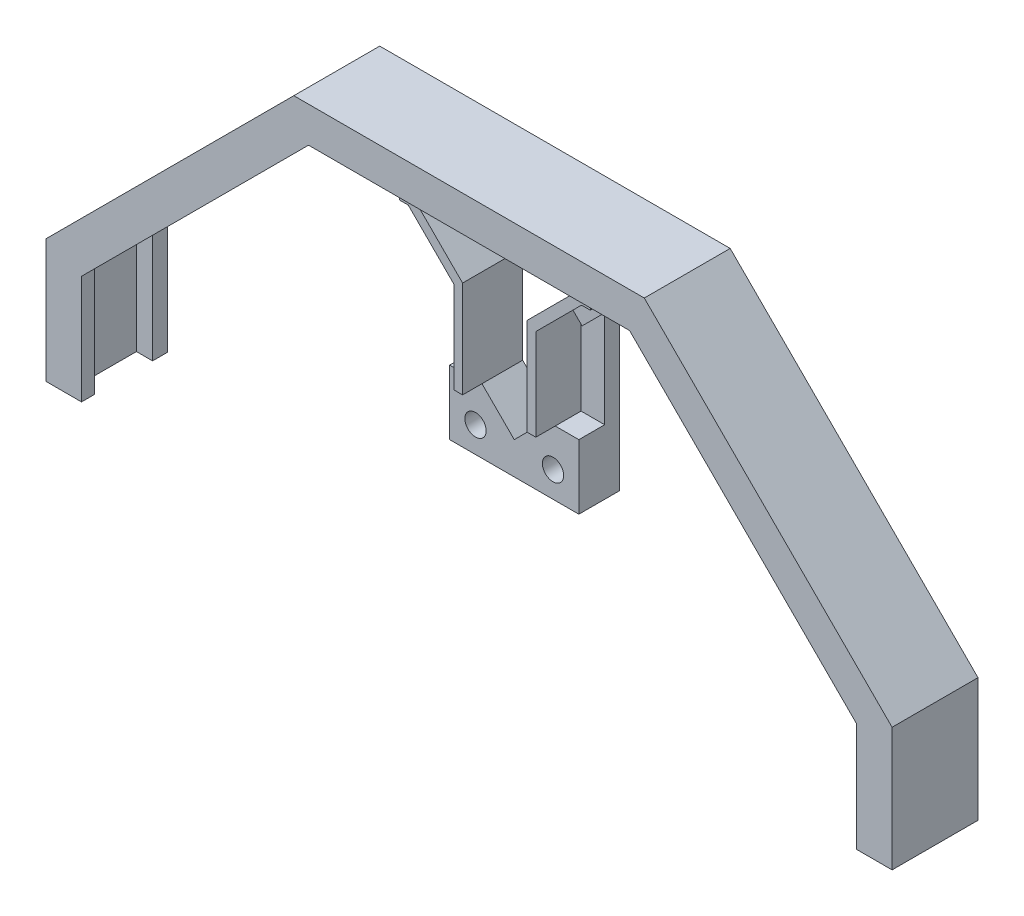
SolidWorks part; units mm, degrees
ref_plane "Plano frontal" through (0, 0, 0) normal (0, 0, 1) x (1, 0, 0)
ref_plane "Plano superior" through (0, 0, 0) normal (0, 1, 0) x (1, 0, 0)
ref_plane "Plano direito" through (0, 0, 0) normal (1, 0, 0) x (0, 0, -1)
sketch "Esboço1" plane through (0, 0, 0) normal (0, 0, 1) x (1, 0, 0)
  line L0 (-50, -22.5) -> (-38, -22.5)
  line L1 (-38, -22.5) -> (-38, 22.5)
  line L2 (-38, 22.5) -> (-50, 22.5)
  line L3 (-50, 22.5) -> (-50, 52.5)
  line L4 (-50, 52.5) -> (-35, 67.5)
  line L5 (-35, 67.5) -> (35, 67.5)
  line L6 (35, 67.5) -> (50, 52.5)
  line L7 (50, 52.5) -> (50, 22.5)
  line L8 (50, 22.5) -> (38, 22.5)
  line L9 (38, 22.5) -> (38, -22.5)
  line L10 (38, -22.5) -> (50, -22.5)
  line L11 (50, -22.5) -> (50, -27.5)
  line L12 (50, -27.5) -> (45, -32.5)
  line L13 (45, -32.5) -> (-45, -32.5)
  line L14 (-45, -32.5) -> (-50, -27.5)
  line L15 (-50, -27.5) -> (-50, -22.5)
  line L16 (-38, 0) -> (38, 0) construction
  line L17 (-33, -9) -> (-33, 0) construction
  line L18 (-33, 0) -> (-33, 9) construction
  line L19 (-33, 9) -> (-38, 9) construction
  line L20 (33.0001, -8.9993) -> (33.0001, 0) construction
  line L21 (33.0001, 0) -> (33, 8.9999) construction
  line L22 (33, 8.9999) -> (38, 8.9999) construction
  circle A0 centre (-33, -9) radius 1.25
  circle A1 centre (-33, 9) radius 1.25
  circle A2 centre (33.0001, -8.9993) radius 1.2496
  circle A3 centre (33, 8.9999) radius 1.2455
  circle A4 centre (-6.75, 62.5) radius 1.2455
  circle A5 centre (6.75, 62.5) radius 1.2455
  circle A6 centre (0, 0) radius 76.0345 construction
  point P54 (0, 0)
sketch "Esboço2" plane through (0, 0, 0) normal (0, 0, 1) x (1, 0, 0)
  line L0 (-50, -27.5) -> (-50, 52.5)
  line L1 (-50, 52.5) -> (-35, 67.5)
  line L2 (-35, 67.5) -> (35, 67.5)
  line L3 (35, 67.5) -> (50, 52.5)
  line L4 (50, 52.5) -> (50, -27.5)
  line L5 (50, -27.5) -> (45, -32.5)
  line L6 (45, -32.5) -> (-45, -32.5)
  line L7 (-45, -32.5) -> (-50, -27.5)
  circle A0 centre (-23.9727, 48.5782) radius 1.2483
  circle A1 centre (-20.797, -17.4645) radius 1.2455
  circle A2 centre (21.113, -17.4645) radius 1.25
  circle A3 centre (24.288, 48.5754) radius 1.25
  point P6 (-35, 67.5)
sketch "Esboço4" plane through (0, 0, 0) normal (0, 0, 1) x (1, 0, 0)
  line L0 (0, 1000) -> (0, 0) construction
  line L1 (-70, 0) -> (-60, 0) construction
  line L2 (70, 0) -> (70, 28.9949)
  line L3 (70, 28.9949) -> (28.9949, 70)
  line L4 (28.9949, 70) -> (-28.9949, 70)
  line L5 (-49.4975, 49.4975) -> (-42.4264, 42.4264) construction
  line L6 (-60, 0) -> (-70, 0)
  line L7 (0, 70) -> (0, 62.1054) construction
  line L8 (-9.8946, 62.1054) -> (9.8946, 62.1054)
  line L9 (9.8946, 62.1054) -> (12.7782, 59.2218)
  line L10 (0, -75) -> (0, -50000) construction
  line L11 (12.7782, 59.2218) -> (12.7782, 57.2218)
  line L12 (12.7782, 57.2218) -> (5, 49.4437)
  line L13 (5, 49.4437) -> (5, 34.4437)
  line L14 (-10, 24.4437) -> (10, 24.4437)
  line L15 (10, 24.4437) -> (10, 49.4437)
  line L16 (10, 49.4437) -> (14.2426, 53.6863)
  line L17 (49.4975, 49.4975) -> (42.4264, 42.4264) construction
  line L18 (42.4264, 42.4264) -> (31.1665, 53.6863)
  line L19 (14.2426, 53.6863) -> (31.1665, 53.6863)
  line L20 (70, 0) -> (60, 0) construction
  line L21 (60, 0) -> (60, 24.8528)
  line L22 (42.4264, 42.4264) -> (60, 24.8528)
  line L23 (60, 0) -> (70, 0)
  line L24 (-42.4264, 42.4264) -> (-60, 24.8528)
  line L25 (-60, 0) -> (-60, 24.8528)
  line L26 (-14.2426, 53.6863) -> (-31.1665, 53.6863)
  line L27 (-42.4264, 42.4264) -> (-31.1665, 53.6863)
  line L28 (-10, 49.4437) -> (-14.2426, 53.6863)
  line L29 (-10, 24.4437) -> (-10, 49.4437)
  line L30 (10, 24.4437) -> (6, 24.4437) construction
  line L31 (-5, 49.4437) -> (-5, 34.4437)
  line L32 (-12.7782, 57.2218) -> (-5, 49.4437)
  line L33 (-12.7782, 59.2218) -> (-12.7782, 57.2218)
  line L34 (-9.8946, 62.1054) -> (-12.7782, 59.2218)
  line L35 (-70, 28.9949) -> (-28.9949, 70)
  line L36 (-70, 0) -> (-70, 28.9949)
  line L37 (6, 24.4437) -> (6, 28.4437) construction
  line L38 (0, 29.4437) -> (-5, 34.4437)
  line L39 (0, 29.4437) -> (5, 34.4437)
  line L62 (-30.458, -68.5369) -> (-8.4911, -90.5039) [skipped]
  line L63 (-26.9258, -70) -> (4.1402, -70) [skipped]
  line L64 (68.5369, -30.458) -> (90.5039, -8.4911) [skipped]
  line L65 (-49.4975, 49.4975) -> (-70, 28.9949) [skipped]
  line L66 (-70, 28.9949) -> (-70, 0) [skipped]
  arc A0 (70, 0) -> (-70, 0) centre (0, 0) ccw construction
  circle A1 centre (6, 28.4437) radius 1.65
  circle A2 centre (-6, 28.4437) radius 1.65
  dimension "D1" = 140
  dimension "D2" = 10
  dimension "D3" = 10
extrude "Ressalto-extrusão1" add sketch "Esboço4" along normal blind 2.3
sketch "Esboço6" plane through (0, 0, 2.3) normal (0, 0, 1) x (1, 0, 0)
  line L0 (-10, 49.4437) -> (-14.2426, 53.6863)
  line L1 (-14.2426, 53.6863) -> (-31.1665, 53.6863)
  line L2 (-31.1665, 53.6863) -> (-35.4092, 49.4437)
  line L3 (-60, 24.8528) -> (-31.1665, 53.6863) construction
  line L4 (-35.4092, 49.4437) -> (-36.8234, 50.8579)
  line L5 (8.5858, 50.8579) -> (13.4142, 55.6863)
  line L6 (-36.8234, 50.8579) -> (-31.9949, 55.6863)
  line L7 (-31.1665, 55.6863) -> (-31.9949, 55.6863)
  line L8 (-31.1665, 55.6863) -> (-13.4142, 55.6863)
  line L9 (-10, 49.4437) -> (-8.5858, 50.8579)
  line L10 (-8.5858, 50.8579) -> (-13.4142, 55.6863)
  line L11 (0, 24.4437) -> (0, 70) construction
  line L12 (-10, 24.4437) -> (10, 24.4437) construction
  line L13 (28.9949, 70) -> (-28.9949, 70) construction
  line L14 (10, 49.4437) -> (8.5858, 50.8579)
  line L15 (31.1665, 55.6863) -> (13.4142, 55.6863)
  line L16 (31.1665, 55.6863) -> (31.9949, 55.6863)
  line L17 (36.8234, 50.8579) -> (31.9949, 55.6863)
  line L18 (35.4092, 49.4437) -> (36.8234, 50.8579)
  line L19 (31.1665, 53.6863) -> (35.4092, 49.4437)
  line L20 (14.2426, 53.6863) -> (31.1665, 53.6863)
  line L21 (10, 49.4437) -> (14.2426, 53.6863)
  dimension "D1" = 2
  dimension "D2" = 2
  dimension "D3" = 2
extrude "Ressalto-extrusão2" add sketch "Esboço6" along normal blind 3.5
sketch "Esboço7" plane through (0, 0, 2.3) normal (0, 0, 1) x (1, 0, 0)
  line L0 (27.131, 65.5) -> (-27.131, 65.5)
  line L1 (-27.131, 65.5) -> (-65.5, 27.131)
  line L2 (-65.5, 27.131) -> (-65.5, 0)
  line L3 (25.8883, 62.5) -> (-25.8883, 62.5)
  line L4 (-25.8883, 62.5) -> (-62.5, 25.8883)
  line L5 (-62.5, 25.8883) -> (-62.5, 0)
  line L6 (-65.5, 0) -> (-62.5, 0)
  line L7 (0, 70) -> (0, 44.5668) construction
  line L8 (28.9949, 70) -> (-28.9949, 70) construction
  line L9 (-70, 28.9949) -> (-70, 0) construction
  line L10 (-28.9949, 70) -> (-70, 28.9949) construction
  line L11 (28.9949, 70) -> (-28.9949, 70) construction
  line L12 (-70, 28.9949) -> (-70, 0) construction
  line L13 (-28.9949, 70) -> (-70, 28.9949) construction
  line L14 (0, 70) -> (-28.9949, 70) construction
  line L15 (28.9949, 65.5) -> (-27.131, 65.5) construction
  line L16 (28.9949, 62.5) -> (-25.8883, 62.5) construction
  line L17 (65.5, 0) -> (62.5, 0)
  line L18 (62.5, 25.8883) -> (62.5, 0)
  line L19 (65.5, 27.131) -> (65.5, 0)
  line L20 (25.8883, 62.5) -> (62.5, 25.8883)
  line L21 (27.131, 65.5) -> (65.5, 27.131)
  point P15 (0, 62.5)
  point P18 (0, 65.5)
  dimension "D1" = 4.5
  dimension "D2" = 3
extrude "Ressalto-extrusão3" add sketch "Esboço7" along normal blind 11
sketch "Esboço8" plane through (0, 0, 2.3) normal (0, 0, 1) x (1, 0, 0)
  line L0 (-65.5, 0) -> (-65.5, 27.131)
  line L1 (-65.5, 27.131) -> (-27.131, 65.5)
  line L2 (-27.131, 65.5) -> (27.131, 65.5)
  line L3 (27.131, 65.5) -> (-27.131, 65.5) construction
  line L4 (0, 65.5) -> (0, 81.0848) construction
  line L5 (91.7639, 81.0848) -> (-91.7639, 81.0848)
  line L6 (-91.7639, 81.0848) -> (-91.7639, -7.4732)
  line L7 (-91.7639, -7.4732) -> (-65.5, -7.4732)
  line L8 (-65.5, -7.4732) -> (-65.5, 0)
  line L9 (65.5, -7.4732) -> (65.5, 0)
  line L10 (91.7639, -7.4732) -> (65.5, -7.4732)
  line L11 (91.7639, 81.0848) -> (91.7639, -7.4732)
  line L12 (65.5, 27.131) -> (27.131, 65.5)
  line L13 (65.5, 0) -> (65.5, 27.131)
extrude "Corte-extrusão1" cut sketch "Esboço8" against normal blind 10.5
sketch "Esboço9" plane through (0, 0, 0) normal (0, 0, -1) x (-1, 0, 0)
  line L0 (60, 0) -> (70, 0)
  line L1 (70, 0) -> (70, 8.0006)
  line L2 (70, 8.0006) -> (-93.2983, 8.0006)
  line L3 (-93.2983, 8.0006) -> (-93.2983, 0)
  line L4 (-93.2983, 0) -> (60, 0)
extrude "Corte-extrusão2" cut sketch "Esboço9" against normal blind 40.5
sketch "Esboço10" plane through (0, 0, 13.3) normal (0, 0, 1) x (1, 0, 0)
  line L0 (-62.5, 8.0006) -> (-62.5, 25.8883) construction
  line L1 (-62.5, 25.8883) -> (-25.8883, 62.5) construction
  line L2 (-25.8883, 62.5) -> (25.8883, 62.5) construction
  line L3 (25.8883, 62.5) -> (62.5, 25.8883) construction
  line L4 (62.5, 25.8883) -> (62.5, 8.0006) construction
  line L5 (-62.5, 8.0006) -> (-62.5, 25.8883)
  line L6 (-62.5, 25.8883) -> (-25.8883, 62.5)
  line L7 (-25.8883, 62.5) -> (25.8883, 62.5)
  line L8 (25.8883, 62.5) -> (62.5, 25.8883)
  line L9 (62.5, 25.8883) -> (62.5, 8.0006)
  line L10 (-60, 8.0006) -> (-60, 24.8528)
  line L11 (-60, 24.8528) -> (-24.8528, 60)
  line L12 (-24.8528, 60) -> (24.8528, 60)
  line L13 (24.8528, 60) -> (60, 24.8528)
  line L14 (60, 24.8528) -> (60, 8.0006)
  line L15 (-62.5, 8.0006) -> (-60, 8.0006)
  line L16 (60, 8.0006) -> (62.5, 8.0006)
  dimension "D1" = 2.5
extrude "Ressalto-extrusão4" add sketch "Esboço10" against normal blind 2
chamfer "Chanfro1" distance 1 angle 45 5 edges at (-62.5, 16.9445, 11.3) (-44.1942, 44.1942, 11.3) (0, 62.5, 11.3) (44.1942, 44.1942, 11.3) (62.5, 16.9445, 11.3)
sketch "Esboço11" plane through (0, 0, 2.3) normal (0, 0, 1) x (1, 0, 0)
  line L0 (-10, 24.4437) -> (10, 24.4437)
  line L1 (10, 24.4437) -> (10, 34.4437)
  line L2 (10, 24.4437) -> (10, 49.4437) construction
  line L3 (10, 34.4437) -> (5, 34.4437)
  line L4 (5, 34.4437) -> (0, 29.4437)
  line L5 (0, 29.4437) -> (-5, 34.4437)
  line L6 (-5, 34.4437) -> (-10, 34.4437)
  line L7 (-10, 49.4437) -> (-10, 24.4437) construction
  line L8 (-10, 34.4437) -> (-10, 24.4437)
  circle A0 centre (-6, 28.4437) radius 1.65
  circle A1 centre (6, 28.4437) radius 1.65
extrude "Ressalto-extrusão5" add sketch "Esboço11" along normal blind 4
sketch "Esboço12" plane through (0, 0, 2.3) normal (0, 0, 1) x (1, 0, 0)
  line L0 (-5, 34.4437) -> (-5, 49.4437)
  line L1 (-5, 49.4437) -> (-12.7782, 57.2218)
  line L2 (-12.7782, 57.2218) -> (-12.7782, 62.9364)
  line L3 (-12.7782, 62.9364) -> (-14.7782, 62.9364)
  line L4 (-14.7782, 62.9364) -> (-14.7782, 55.6863)
  line L5 (-14.7782, 55.6863) -> (-13.4142, 55.6863)
  line L6 (-13.4142, 55.6863) -> (-6.3431, 48.6152)
  line L7 (-6.3431, 48.6152) -> (-6.3431, 34.4437)
  line L8 (-6.3431, 34.4437) -> (-5, 34.4437)
  line L9 (0, 29.4437) -> (0, 60) construction
  line L10 (6.3431, 34.4437) -> (5, 34.4437)
  line L11 (6.3431, 48.6152) -> (6.3431, 34.4437)
  line L12 (13.4142, 55.6863) -> (6.3431, 48.6152)
  line L13 (14.7782, 55.6863) -> (13.4142, 55.6863)
  line L14 (14.7782, 62.9364) -> (14.7782, 55.6863)
  line L15 (12.7782, 62.9364) -> (14.7782, 62.9364)
  line L16 (12.7782, 57.2218) -> (12.7782, 62.9364)
  line L17 (5, 49.4437) -> (12.7782, 57.2218)
  line L18 (5, 34.4437) -> (5, 49.4437)
  point P20 (0, 29.4437)
extrude "Ressalto-extrusão6" add sketch "Esboço12" along normal blind 7
